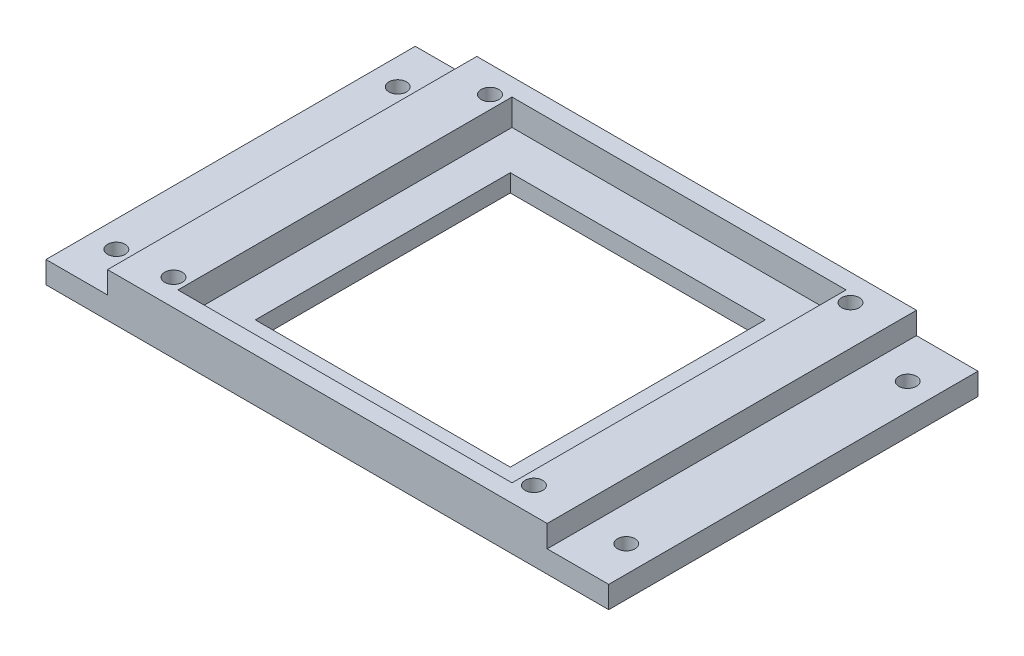
SolidWorks part; units mm, degrees
ref_plane "Front Plane" through (0, 0, 0) normal (0, 0, 1) x (1, 0, 0)
ref_plane "Top Plane" through (0, 0, 0) normal (0, 1, 0) x (1, 0, 0)
ref_plane "Right Plane" through (0, 0, 0) normal (1, 0, 0) x (0, 0, -1)
sketch "Sketch1" plane through (0, 0, 0) normal (1, 0, 0) x (0, 0, -1)
  circle A0 centre (0, 0) radius 7.5
  circle A1 centre (0, 0) radius 11
extrude "Extrude-Thin1" add sketch "Sketch1" along normal blind 10 thin contours A0
sketch "Sketch3" plane through (0, 0, 0) normal (1, 0, 0) x (0, 0, -1)
  line L1 (-11, 0) -> (-11, 30)
  line L2 (11, 0) -> (11, 30)
  line L3 (-11, 30) -> (11, 30)
  arc A1 (11, 0) -> (-11, 0) centre (0, 0) ccw
  point P1 (0, 0)
extrude "Boss-Extrude2" add sketch "Sketch3" along normal blind 10
sketch "Sketch6" plane through (0, 0, 11) normal (0, 0, 1) x (1, 0, 0)
  line L0 (10, 30) -> (10, 0) construction
  line L1 (0, 30) -> (10, 30)
  line L2 (0, 30) -> (0, 25)
  line L3 (0, 25) -> (10, 25)
  line L4 (10, 30) -> (10, 25)
extrude "Boss-Extrude3" add sketch "Sketch6" along normal blind 10
sketch "Sketch8" plane through (0, 0, -11) normal (0, 0, -1) x (-1, 0, 0)
  line L0 (0, 0) -> (0, 30) construction
  line L1 (-10, 30) -> (0, 30)
  line L2 (-10, 30) -> (-10, 25)
  line L3 (-10, 25) -> (0, 25)
  line L4 (0, 30) -> (0, 25)
extrude "Boss-Extrude4" add sketch "Sketch8" along normal blind 10
sketch "Sketch9" plane through (0, 0, 0) normal (-1, 0, 0) x (0, 0, 1)
  line L1 (-21, 30) -> (21, 30)
  line L2 (-21, 30) -> (-21, 25)
  line L3 (-21, 25) -> (21, 25)
  line L4 (21, 30) -> (21, 25)
extrude "Boss-Extrude5" add sketch "Sketch9" along normal blind 54
sketch "Sketch19" plane through (0, 30, 0) normal (0, 1, 0) x (1, 0, 0)
  line L7 (-41, 19) -> (-3, 19)
  line L8 (-41, 19) -> (-41, -19)
  line L9 (-3, 19) -> (-3, -19)
  line L10 (-41, -19) -> (-3, -19)
  line L11 (-41, 19) -> (-3, -19) construction
  line L12 (-3, 19) -> (-41, -19) construction
extrude "Cut-Extrude3" cut sketch "Sketch19" against normal blind 3
sketch "Sketch25" plane through (0, 27, 0) normal (0, 1, 0) x (1, 0, 0)
  line L5 (-36.645, -14.5492) -> (-7.645, -14.5492)
  line L6 (-36.645, -14.5492) -> (-36.645, 14.4508)
  line L7 (-36.645, 14.4508) -> (-7.645, 14.4508)
  line L8 (-7.645, -14.5492) -> (-7.645, 14.4508)
  line L9 (-36.645, -14.5492) -> (-7.645, 14.4508) construction
  line L10 (-36.645, 14.4508) -> (-7.645, -14.5492) construction
extrude "Cut-Extrude4" cut sketch "Sketch25" against normal blind 2
sketch "Sketch26" plane through (0, 30, 0) normal (0, 1, 0) x (1, 0, 0)
  circle A0 centre (-1.5, 17.9974) radius 1.0026
extrude "Cut-Extrude5" cut sketch "Sketch26" against normal blind 3
pattern_linear "LPattern4" count 2 spacing 36 along (0, 0, 1) count 2 spacing 41 along (-1, 0, 0) of "Cut-Extrude5"
sketch "Sketch29" plane through (10, 0, 0) normal (1, 0, 0) x (0, 0, -1)
  line L1 (-11, 25) -> (11, 25)
  line L2 (-11, 25) -> (-11, -11)
  line L3 (-11, -11) -> (11, -11)
  line L4 (11, 25) -> (11, -11)
extrude "Cut-Extrude8" cut sketch "Sketch29" against normal blind 10
sketch "Sketch35" plane through (0, 30, 0) normal (0, 1, 0) x (1, 0, 0)
  circle A1 centre (7, 16) radius 1
extrude "Cut-Extrude9" cut sketch "Sketch35" against normal blind 5
pattern_linear "LPattern5" count 2 spacing 58 along (-1, 0, 0) count 2 spacing 32 along (0, 0, 1) of "Cut-Extrude9"
sketch "Sketch37" plane through (10, 0, 0) normal (1, 0, 0) x (0, 0, -1)
  line L0 (-21, 25) -> (-21, 30) construction
  line L1 (21, 30) -> (-21, 30)
  line L2 (21, 30) -> (21, 27.5)
  line L3 (21, 27.5) -> (-21, 27.5)
  line L4 (-21, 30) -> (-21, 27.5)
extrude "Cut-Extrude10" cut sketch "Sketch37" against normal blind 5
sketch "Sketch38" plane through (-54, 0, 0) normal (-1, 0, 0) x (0, 0, 1)
  line L1 (-21, 30) -> (21, 30)
  line L2 (-21, 30) -> (-21, 27.5)
  line L3 (-21, 27.5) -> (21, 27.5)
  line L4 (21, 30) -> (21, 27.5)
extrude "Cut-Extrude11" cut sketch "Sketch38" against normal blind 5
sketch "Sketch39" plane through (0, 30, 0) normal (0, 1, 0) x (1, 0, 0)
  line L0 (-49, -21) -> (-47.0017, -21)
  line L1 (5, -21) -> (-49, -21) construction
  line L2 (-47.0017, -21) -> (-47.0017, 21)
  line L3 (-49, 21) -> (5, 21) construction
  line L4 (-47.0017, 21) -> (-49, 21)
  line L5 (-49, 21) -> (-49, -21)
extrude "Cut-Extrude12" cut sketch "Sketch39" against normal blind 2.5
sketch "Sketch41" plane through (0, 30, 0) normal (0, 1, 0) x (1, 0, 0)
  line L0 (5, -21) -> (3.0021, -21)
  line L1 (5, -21) -> (-47.0017, -21) construction
  line L2 (3.0021, -21) -> (3.0021, 21)
  line L3 (-47.0017, 21) -> (5, 21) construction
  line L4 (3.0021, 21) -> (5, 21)
  line L5 (5, 21) -> (5, -21)
extrude "Cut-Extrude13" cut sketch "Sketch41" against normal blind 2.5
